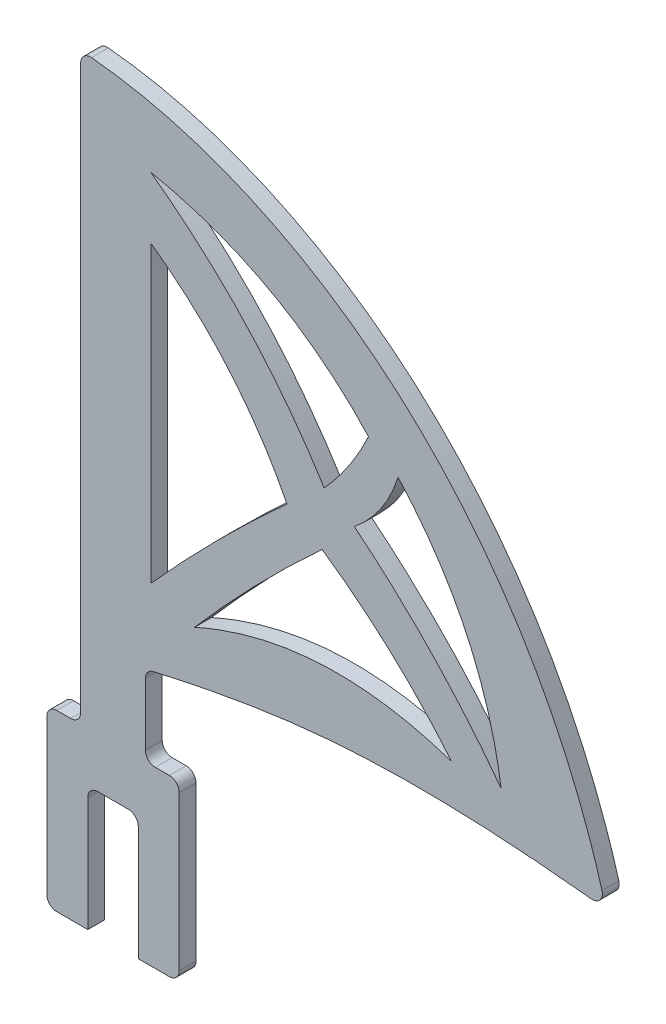
SolidWorks part; units mm, degrees
ref_plane "Front Plane" through (0, 0, 0) normal (0, 0, 1) x (1, 0, 0)
ref_plane "Top Plane" through (0, 0, 0) normal (0, 1, 0) x (1, 0, 0)
ref_plane "Right Plane" through (0, 0, 0) normal (1, 0, 0) x (0, 0, -1)
sketch "Sketch1" plane through (0, 0, 0) normal (0, 0, 1) x (1, 0, 0)
  line L0 (-22.1564, 60.7737) -> (30.4457, 60.7737) construction
  line L1 (-16.891, -22.225) -> (16.891, -22.225)
  line L2 (-16.891, -22.225) -> (-16.891, 22.225)
  line L3 (-16.891, 22.225) -> (16.891, 22.225)
  line L4 (16.891, -22.225) -> (16.891, 22.225)
  line L5 (-16.891, -22.225) -> (16.891, 22.225) construction
  line L6 (-16.891, 22.225) -> (16.891, -22.225) construction
  line L7 (-8.255, 0) -> (8.255, 0)
  line L8 (-8.255, 0) -> (-8.255, 146.05)
  line L9 (-8.255, 146.05) -> (8.255, 146.05)
  line L10 (8.255, 0) -> (8.255, 146.05)
  line L11 (-39.8263, 94.1046) -> (105.507, 94.1046) construction
  line L12 (-8.255, 171.082) -> (-8.255, 146.05)
  spline S0 degree 3 poles (-8.255, 171.082) (8.4825, 169.9208) (37.6961, 161.352) (91.6785, 125.0407) (116.9301, 81.49) (125.7166, 48.3738) knots 0 0 0 0 0.260197 0.464601 1 1 1 1
  spline S1 degree 3 poles (125.7166, 48.3738) (101.4544, 51.0517) (61.6707, 53.3849) (22.7589, 46.057) (8.255, 42.6449) knots 0 0 0 0 0.621556 1 1 1 1
  point P0 (0, 0)
  dimension "D1" = 33.782
  dimension "D2" = 44.45
  dimension "D3" = 16.51
  dimension "D4" = 146.05
extrude "Boss-Extrude1" add sketch "Sketch1" along normal blind 4.2926 contours S1 S0 L12 L9 L10 | L3 L10 L9 L8 | L7 L10 L3 L8 | L10 L7 L8 L3 L2 L1 L4
fillet "Fillet1" radius 2.54 7 edges at (-8.255, 22.225, 2.1463) (8.255, 42.6449, 2.1463) (8.255, 22.225, 2.1463) (16.891, 22.225, 2.1463) (16.891, -22.225, 2.1463) (-16.891, -22.225, 2.1463) (-16.891, 22.225, 2.1463)
sketch "Sketch3" plane through (0, 0, 4.2926) normal (0, 0, 1) x (1, 0, 0)
  line L0 (-14.351, -22.225) -> (14.351, -22.225) construction
  line L1 (6.4389, -22.225) -> (-6.4389, -22.225)
  line L2 (6.4389, -22.225) -> (6.4389, 9.525)
  line L3 (6.4389, 9.525) -> (-6.4389, 9.525)
  line L4 (-6.4389, -22.225) -> (-6.4389, 9.525)
  line L5 (0, 9.525) -> (0, -22.225) construction
  dimension "D1" = 12.8778
  dimension "D2" = 31.75
extrude "Cut-Extrude1" cut sketch "Sketch3" against normal blind 4.2926
fillet "Fillet2" radius 2.54 4 edges at (6.4389, 9.525, 2.1463) (-6.4389, 9.525, 2.1463) (125.7166, 48.3738, 2.1463) (-8.255, 171.082, 2.1463)
sketch "Sketch4" plane through (0, 0, 0) normal (0, 0, -1) x (-1, 0, 0)
  line L5 (-9.6223, 62.2796) -> (-9.6223, 137.4549)
  spline S0 degree 2 poles (-65.1718, 122.4571) (-42.9913, 146.4196) (-9.6223, 153.0952) knots 0 0 0 1 1 1
  spline S1 degree 2 poles (-72.704, 117.2894) (-94.4178, 93.4728) (-98.9883, 61.6736) knots 0 0 0 1 1 1
  spline S2 degree 2 poles (-98.9883, 61.6736) (-82.6984, 83.6577) (-61.5335, 100.7949) knots 0 0 0 1 1 1
  spline S3 degree 2 poles (-9.6223, 153.0952) (-36.4257, 133.502) (-53.8623, 105.4665) knots 0 0 0 1 1 1
  spline S4 degree 2 poles (-9.6223, 137.4549) (-31.9763, 121.6157) (-44.3599, 97.1932) knots 0 0 0 1 1 1
  spline S5 degree 2 poles (-86.3212, 61.3031) (-71.9555, 78.7744) (-53.3297, 91.6168) knots 0 0 0 1 1 1
  spline S6 degree 2 poles (-86.3212, 61.3031) (-52.8981, 72.5832) (-20.7923, 58.1714) knots 0 0 0 1 1 1
  spline S7 degree 2 poles (-53.3297, 91.6168) (-36.0842, 75.8473) (-20.7923, 58.1714) knots 0 0 0 1 1 1
  spline S8 degree 2 poles (-72.704, 117.2894) (-69.576, 107.2714) (-61.5335, 100.7949) knots 0 0 0 1 1 1
  spline S9 degree 2 poles (-65.1718, 122.4571) (-60.7818, 113.0769) (-53.8623, 105.4665) knots 0 0 0 1 1 1
  spline S10 degree 2 poles (-44.3599, 97.1932) (-26.0739, 80.6433) (-9.6223, 62.2796) knots 0 0 0 1 1 1
extrude "Cut-Extrude2" cut sketch "Sketch4" against normal blind 4.2926
